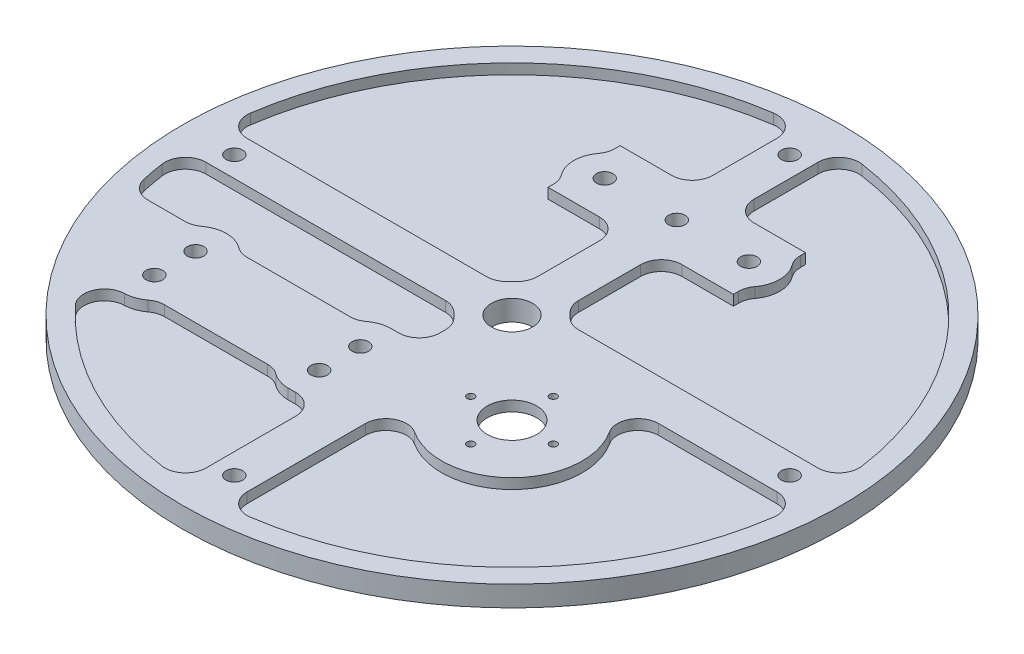
SolidWorks part; units mm, degrees
ref_plane "Front Plane" through (0, 0, 0) normal (0, 0, 1) x (1, 0, 0)
ref_plane "Top Plane" through (0, 0, 0) normal (0, 1, 0) x (1, 0, 0)
ref_plane "Right Plane" through (0, 0, 0) normal (1, 0, 0) x (0, 0, -1)
sketch "Sketch3" plane through (0, 0, 0) normal (0, 1, 0) x (1, 0, 0)
  circle A0 centre (0, 0) radius 101.6
  dimension "D1" = 203.2
extrude "Boss-Extrude1" add sketch "Sketch3" along normal blind 6.35
sketch "Sketch4" plane through (0, 6.35, 0) normal (0, 1, 0) x (1, 0, 0)
  line L0 (0, 0) -> (71.842, -71.842) construction
  line L1 (71.842, -71.842) -> (71.842, 0)
  line L2 (71.842, 0) -> (0, 0)
  line L3 (71.842, -71.842) -> (0, -71.842)
  line L4 (0, -71.842) -> (0, 0)
  line L5 (-85.5998, 0) -> (85.5998, 0) construction
  line L6 (0, 85.5998) -> (0, -85.5998) construction
  line L7 (-85.5998, 0) -> (0, 85.5998)
  line L8 (0, 85.5998) -> (85.5998, 0)
  line L9 (85.5998, 0) -> (0, -85.5998)
  line L10 (0, -85.5998) -> (-85.5998, 0)
  line L11 (37.404, -31.4746) -> (31.4746, -37.404)
  line L12 (24.652, -18.7226) -> (18.7226, -24.652)
  circle A0 centre (0, 0) radius 6.35
  circle A1 centre (0, 0) radius 101.6
  circle A2 centre (28.0633, -28.0633) radius 7.62
  circle A3 centre (28.0633, -28.0633) radius 9.9441
  dimension "D1" = 12.7
  dimension "D2" = 203.2
  dimension "D4" = 39.6875
  dimension "D5" = 15.24
  dimension "D8" = 19.8882
  dimension "D9" = 18.034
  dimension "D3" = 71.842
  dimension "D6" = 171.1996
  dimension "D7" = 171.1996
extrude "Cut-Extrude1" cut sketch "Sketch4" against normal through all contours L2 A0 L4 | L4 A0 L2 | A2
hole_wizard "1/4-20 Tapped Hole5" positions "3DSketch1" profile "Sketch5" tap size "1/4-20" standard "ANSI Inch"
sketch3d "3DSketch1"
  point P0 (0, 6.35, -85.5998)
  point P3 (-85.5998, 6.35, 0)
  point P6 (0, 6.35, 85.5998)
  point P9 (85.5998, 6.35, 0)
sketch "Sketch5" plane through (0, 6.35, -85.5998) normal (1, 0, 0) x (0, 0, 1)
  line L0 (0, 0) -> (0, 20.5838)
  line L1 (0, 20.5838) -> (2.5527, 19.05)
  line L2 (2.5527, 19.05) -> (2.5527, 0)
  line L5 (2.5527, 0) -> (0, 0)
  line L10 (0, 20.5838) -> (-2.5527, 19.05) construction
  line L11 (0, -6.35) -> (0, 107.95) construction
  dimension "Tap Drill Dia." = 5.1054
  dimension "Tap Drill Depth" = 19.05
  dimension "Drill Angle" = 118
cosmetic thread "Hole Thread1" parameters "D1"=6.35, "D2"=6.35
cosmetic thread "Hole Thread2" parameters "D1"=6.35, "D2"=6.35
cosmetic thread "Hole Thread3" parameters "D1"=6.35, "D2"=6.35
cosmetic thread "Hole Thread4" parameters "D1"=6.35, "D2"=6.35
sketch "Sketch6" plane through (0, 6.35, 0) normal (0, 1, 0) x (1, 0, 0)
  line L0 (-9.525, 50.8) -> (9.525, 50.8) construction
  line L1 (-15.875, 61.9125) -> (-9.525, 61.9125)
  line L2 (-15.875, 61.9125) -> (-15.875, 39.6875)
  line L3 (-15.875, 39.6875) -> (-9.525, 39.6875)
  line L4 (-9.525, 61.9125) -> (-9.525, 39.6875)
  line L5 (9.525, 61.9125) -> (15.875, 61.9125)
  line L6 (9.525, 61.9125) -> (9.525, 39.6875)
  line L7 (9.525, 39.6875) -> (15.875, 39.6875)
  line L8 (15.875, 61.9125) -> (15.875, 39.6875)
  line L9 (-27.7114, -25.4) -> (-21.3614, -25.4)
  line L10 (-59.4614, -25.4) -> (-53.1114, -25.4)
  line L11 (-59.4614, -25.4) -> (-59.4614, -50.8)
  line L12 (-59.4614, -50.8) -> (-53.1114, -50.8)
  line L13 (-53.1114, -25.4) -> (-53.1114, -50.8)
  line L14 (-27.7114, -25.4) -> (-27.7114, -50.8)
  line L15 (-27.7114, -50.8) -> (-21.3614, -50.8)
  line L16 (-21.3614, -25.4) -> (-21.3614, -50.8)
  line L17 (-53.1114, -38.1) -> (-27.7114, -38.1) construction
  line L18 (0, 101.6) -> (0, -101.6) construction
  line L19 (-101.6, 0) -> (101.6, 0) construction
  line L20 (6.35, 0) -> (6.35, -101.4014)
  line L21 (-6.35, 0) -> (-6.35, -101.4014)
  line L22 (-6.35, 0) -> (-6.35, 101.4014)
  line L23 (6.35, 0) -> (6.35, 101.4014)
  line L24 (0, 6.35) -> (101.4014, 6.35)
  line L25 (0, -6.35) -> (101.4014, -6.35)
  line L26 (0, 6.35) -> (-101.4014, 6.35)
  line L27 (0, -6.35) -> (-101.4014, -6.35)
  line L28 (-15.875, 50.8) -> (-28.575, 50.8) construction
  line L29 (-28.575, 61.9125) -> (28.575, 61.9125)
  line L30 (-28.575, 61.9125) -> (-28.575, 39.6875)
  line L31 (-28.575, 39.6875) -> (28.575, 39.6875)
  line L32 (28.575, 61.9125) -> (28.575, 39.6875)
  line L33 (-72.1614, -25.4) -> (-21.3614, -25.4)
  line L34 (-72.1614, -25.4) -> (-72.1614, -50.8) construction
  line L35 (-72.1614, -50.8) -> (-21.3614, -50.8)
  line L36 (-15.0114, -53.975) -> (-6.35, -53.975)
  line L37 (15.875, 50.8) -> (28.575, 50.8) construction
  line L38 (-59.4614, -50.8) -> (-21.3614, -50.8)
  line L39 (-21.3614, -25.4) -> (-6.35, -25.4)
  line L40 (-21.3614, -25.4) -> (-21.3614, -50.8)
  line L41 (-21.3614, -50.8) -> (-6.35, -50.8)
  line L42 (-6.35, -25.4) -> (-6.35, -50.8)
  line L43 (-15.0114, -22.225) -> (-6.35, -22.225)
  line L44 (-72.1614, -25.4) -> (-91.8009, -25.4)
  line L45 (-72.1614, -50.8) -> (-80.5725, -50.8)
  line L46 (-6.35, -50.8) -> (-6.3248, -50.8431)
  line L47 (-72.1614, -50.8) -> (-59.4614, -50.8)
  line L48 (-65.8114, -53.975) -> (-78.481, -53.975)
  circle A0 centre (28.0633, -28.0633) radius 12.7
  circle A1 centre (0, 0) radius 95.25
  circle A2 centre (0, 0) radius 101.6 construction
  circle A3 centre (85.5998, 0) radius 6.35
  circle A4 centre (0, -85.5998) radius 6.35
  circle A5 centre (-85.5998, 0) radius 6.35
  circle A6 centre (0, 85.5998) radius 6.35
  circle A7 centre (0, 0) radius 12.7
  circle A8 centre (0, 0) radius 6.35 construction
  circle A9 centre (-22.225, 50.8) radius 6.35
  circle A10 centre (22.225, 50.8) radius 6.35
  circle A11 centre (28.0633, -28.0633) radius 21.7133
  circle A12 centre (-22.225, 50.8) radius 9.525
  circle A13 centre (22.225, 50.8) radius 9.525
  circle A14 centre (-65.8114, -31.75) radius 9.525
  circle A15 centre (-65.8114, -44.45) radius 9.525
  circle A16 centre (-15.0114, -31.75) radius 9.525
  circle A17 centre (-15.0114, -44.45) radius 9.525
  point P18 (0, 50.8)
  point P22 (-40.4114, -38.1)
  dimension "D12" = 6.35
  dimension "D13" = 12.7
  dimension "D14" = 12.7
  dimension "D15" = 12.7
  dimension "D16" = 12.7
  dimension "D17" = 25.4
  dimension "D18" = 25.4
  dimension "D28" = 12.7
  dimension "D29" = 12.7
  dimension "D19" = 22.225
  dimension "D21" = 19.05
  dimension "D24" = 19.05
  dimension "D26" = 6.35
  dimension "D33" = 19.05
  dimension "D34" = 6.35
  dimension "D35" = 6.35
  dimension "D36" = 6.35
  dimension "D31" = 6.35
  dimension "D25" = 6.35
  dimension "D32" = 19.05
  dimension "D38" = 19.05
  dimension "D39" = 19.05
  dimension "D1" = 19.05
  dimension "D2" = 22.225
  dimension "D3" = 6.35
  dimension "D4" = 6.35
  dimension "D5" = 40.4114
  dimension "D6" = 38.1
  dimension "D7" = 25.4
  dimension "D8" = 6.35
  dimension "D9" = 6.35
  dimension "D10" = 25.4
  dimension "D11" = 88.9
  dimension "D20" = 12.7
  dimension "D22" = 12.7
  dimension "D23" = 12.7
  dimension "D27" = 12.7
  dimension "D30" = 6.35
  dimension "D37" = 6.35
extrude "Cut-Extrude2" cut sketch "Sketch6" against normal blind 3.175
hole_wizard "1/4-20 Tapped Hole2" positions "3DSketch3" profile "Sketch9" tap size "1/4-20" standard "ANSI Inch"
sketch3d "3DSketch3"
  point P0 (-22.225, 6.35, -50.8)
  point P3 (22.225, 6.35, -50.8)
  point P6 (0, 6.35, -50.8)
sketch "Sketch9" plane through (-22.225, 6.35, -50.8) normal (1, 0, 0) x (0, 0, 1)
  line L0 (0, 0) -> (0, 20.5838)
  line L1 (0, 20.5838) -> (2.5527, 19.05)
  line L2 (2.5527, 19.05) -> (2.5527, 0)
  line L5 (2.5527, 0) -> (0, 0)
  line L10 (0, 20.5838) -> (-2.5527, 19.05) construction
  line L11 (0, -6.35) -> (0, 107.95) construction
  dimension "Tap Drill Dia." = 5.1054
  dimension "Tap Drill Depth" = 19.05
  dimension "Drill Angle" = 118
cosmetic thread "Hole Thread7" parameters "D1"=6.35, "D2"=6.35
cosmetic thread "Hole Thread8" parameters "D1"=6.35, "D2"=6.35
cosmetic thread "Hole Thread9" parameters "D1"=6.35, "D2"=6.35
hole_wizard "1/4-20 Tapped Hole4" positions "3DSketch6" profile "Sketch12" tap size "1/4-20" standard "ANSI Inch"
sketch3d "3DSketch6"
  line L5 (-58.7119, 6.35, 50.8) -> (-22.1109, 6.35, 50.8) construction
  line L6 (-58.7119, 6.35, 25.4) -> (-22.1109, 6.35, 25.4) construction
  line L8 (-6.35, 3.175, 10.9985) -> (-6.35, 3.175, 22.225) construction
  line L9 (-6.35, 3.175, 10.9985) -> (-6.35, 3.175, 22.225) construction
  line L10 (-6.35, 3.175, 53.975) -> (-6.35, 3.175, 95.0381) construction
  line L11 (-6.35, 3.175, 10.9985) -> (-6.35, 3.175, 22.225) construction
  point P0 (-65.8114, 6.35, 31.75)
  point P2 (-65.8114, 6.35, 44.45)
  point P4 (-15.0114, 6.35, 44.45)
  point P6 (-15.0114, 6.35, 31.75)
  dimension "D1" = 59.5461
  dimension "D2" = 6.35
  dimension "D3" = 59.5461
  dimension "D4" = 6.35
  dimension "D5" = 6.35
  dimension "D6" = 9.225
  dimension "D7" = 9.225
  dimension "D8" = 6.35
sketch "Sketch12" plane through (-65.8114, 6.35, 31.75) normal (1, 0, 0) x (0, 0, 1)
  line L0 (0, 0) -> (0, 20.5838)
  line L1 (0, 20.5838) -> (2.5527, 19.05)
  line L2 (2.5527, 19.05) -> (2.5527, 0)
  line L5 (2.5527, 0) -> (0, 0)
  line L10 (0, 20.5838) -> (-2.5527, 19.05) construction
  line L11 (0, -6.35) -> (0, 107.95) construction
  dimension "Tap Drill Dia." = 5.1054
  dimension "Tap Drill Depth" = 19.05
  dimension "Drill Angle" = 118
cosmetic thread "Hole Thread14" parameters "D1"=6.35, "D2"=6.35
cosmetic thread "Hole Thread15" parameters "D1"=6.35, "D2"=6.35
cosmetic thread "Hole Thread16" parameters "D1"=6.35, "D2"=6.35
cosmetic thread "Hole Thread17" parameters "D1"=6.35, "D2"=6.35
fillet "Fillet3" radius 6.35 33 edges at (-10.9985, 4.7625, 6.35) (-6.35, 4.7625, 10.9985) (-6.35, 4.7625, 95.0381) (-95.0381, 4.7625, 6.35) (95.0381, 4.7625, 6.35) (6.35, 4.7625, 95.0381) (95.0381, 4.7625, -6.35) (10.9985, 4.7625, -6.35) (6.35, 4.7625, -10.9985) (6.35, 4.7625, -39.6875) (6.35, 4.7625, -61.9125) (6.35, 4.7625, -95.0381) (-6.35, 4.7625, -95.0381) (-95.0381, 4.7625, -6.35) (-10.9985, 4.7625, -6.35) (-6.35, 4.7625, -10.9985) (-6.35, 4.7625, -39.6875) (28.0633, 4.7625, 6.35) (6.35, 4.7625, 28.0633) (-6.35, 4.7625, -61.9125) (-72.9109, 4.7625, 25.4) (-58.7119, 4.7625, 25.4) (-22.1109, 4.7625, 50.8) (-22.1109, 4.7625, 25.4) (-28.575, 4.7625, -57.8995) (-28.575, 4.7625, -43.7005) (28.575, 4.7625, -43.7005) (28.575, 4.7625, -57.8995) (-91.8009, 4.7625, 25.4) (-58.7119, 4.7625, 50.8) (-78.481, 4.7625, 53.975) (-6.35, 4.7625, 22.225) (-6.35, 4.7625, 53.975)
hole_wizard "#4-40 Tapped Hole1" positions "3DSketch7" profile "Sketch13" tap size "#4-40" standard "ANSI Inch" end condition through all
sketch3d "3DSketch7"
  point P0 (28.0633, 6.35, 15.3354)
  point P2 (15.3354, 6.35, 28.0633)
  point P4 (28.0633, 6.35, 40.7912)
  point P6 (40.7912, 6.35, 28.0633)
  dimension "D1" = 12.7279
  dimension "D3" = 12.7279
  dimension "D2" = 12.7279
  dimension "D4" = 12.7279
sketch "Sketch13" plane through (28.0633, 6.35, 15.3354) normal (1, 0, 0) x (0, 0, 1)
  line L0 (0, 0) -> (0, 6.35)
  line L1 (0, 6.35) -> (1.1303, 6.35)
  line L2 (1.1303, 6.35) -> (1.1303, 0)
  line L5 (1.1303, 0) -> (0, 0)
  line L11 (0, -6.35) -> (0, 107.95) construction
  dimension "Thread Major Dia." = 2.2606
  dimension "Thru Tap Drill Depth" = 6.35
sketch "Sketch15" plane through (0, 0, 0) normal (0, -1, 0) x (1, 0, 0)
  line L0 (40.7912, 23.3008) -> (32.8258, 15.3354)
  line L1 (23.3008, 15.3354) -> (15.3354, 23.3008)
  line L2 (15.3354, 32.8258) -> (23.3008, 40.7912)
  line L3 (32.8258, 40.7912) -> (40.7912, 32.8258)
  line L12 (-15.0114, 44.45) -> (-15.0114, 31.75) construction
  line L13 (-8.6614, 44.45) -> (-8.6614, 31.75)
  line L14 (-21.3614, 44.45) -> (-21.3614, 31.75)
  line L15 (-65.8114, 44.45) -> (-65.8114, 31.75) construction
  line L16 (-59.4614, 44.45) -> (-59.4614, 31.75)
  line L17 (-72.1614, 44.45) -> (-72.1614, 31.75)
  arc A0 (-8.6614, 44.45) -> (-21.3614, 44.45) centre (-15.0114, 44.45) ccw
  arc A1 (-21.3614, 31.75) -> (-8.6614, 31.75) centre (-15.0114, 31.75) ccw
  arc A2 (-59.4614, 44.45) -> (-72.1614, 44.45) centre (-65.8114, 44.45) ccw
  arc A3 (-72.1614, 31.75) -> (-59.4614, 31.75) centre (-65.8114, 31.75) ccw
  circle A4 centre (0, -50.8) radius 6.35
  circle A5 centre (-22.225, -50.8) radius 6.35
  circle A6 centre (22.225, -50.8) radius 6.35
  arc A7 (23.3008, 15.3354) -> (32.8258, 15.3354) centre (28.0633, 15.3354) ccw
  arc A8 (40.7912, 23.3008) -> (40.7912, 32.8258) centre (40.7912, 28.0633) ccw
  arc A9 (32.8258, 40.7912) -> (23.3008, 40.7912) centre (28.0633, 40.7912) ccw
  arc A10 (15.3354, 32.8258) -> (15.3354, 23.3008) centre (15.3354, 28.0633) ccw
  point P3 (-15.0114, 38.1)
  point P9 (-65.8114, 38.1)
  circle M4 centre (28.0633, 15.3354) radius 1.1303
  circle M8 centre (15.3354, 28.0633) radius 1.1303
  circle M16 centre (40.7912, 28.0633) radius 1.1303
  dimension "D1" = 9.525
  dimension "D2" = 6.35
  dimension "D3" = 6.35
  dimension "D4" = 9.525
  dimension "D5" = 12.7
  dimension "D6" = 12.7
  dimension "D7" = 12.7
  dimension "D9" = 9.525
  dimension "D8" = 9.525
extrude "Cut-Extrude3" cut sketch "Sketch15" against normal blind 3.175 contours A10 M8 | A7 M4 | A8 M16
fillet "Fillet4" radius 6.35 8 edges at (23.3008, 1.5875, 40.7912) (32.8258, 1.5875, 40.7912) (40.7912, 1.5875, 32.8258) (32.8258, 1.5875, 15.3354) (23.3008, 1.5875, 15.3354) (15.3354, 1.5875, 23.3008) (15.3354, 1.5875, 32.8258) (40.7912, 1.5875, 23.3008)
sketch "Sketch16" plane through (0, 6.35, 0) normal (0, 1, 0) x (1, 0, 0)
  line L1 (-63.5, 63.5) -> (63.5, 63.5)
  line L2 (-63.5, 63.5) -> (-63.5, -63.5)
  line L3 (-63.5, -63.5) -> (63.5, -63.5)
  line L4 (63.5, 63.5) -> (63.5, -63.5)
  line L5 (-63.5, 63.5) -> (63.5, -63.5) construction
  line L6 (-63.5, -63.5) -> (63.5, 63.5) construction
  point P0 (0, 0)
  dimension "D1" = 127
  dimension "D2" = 127
